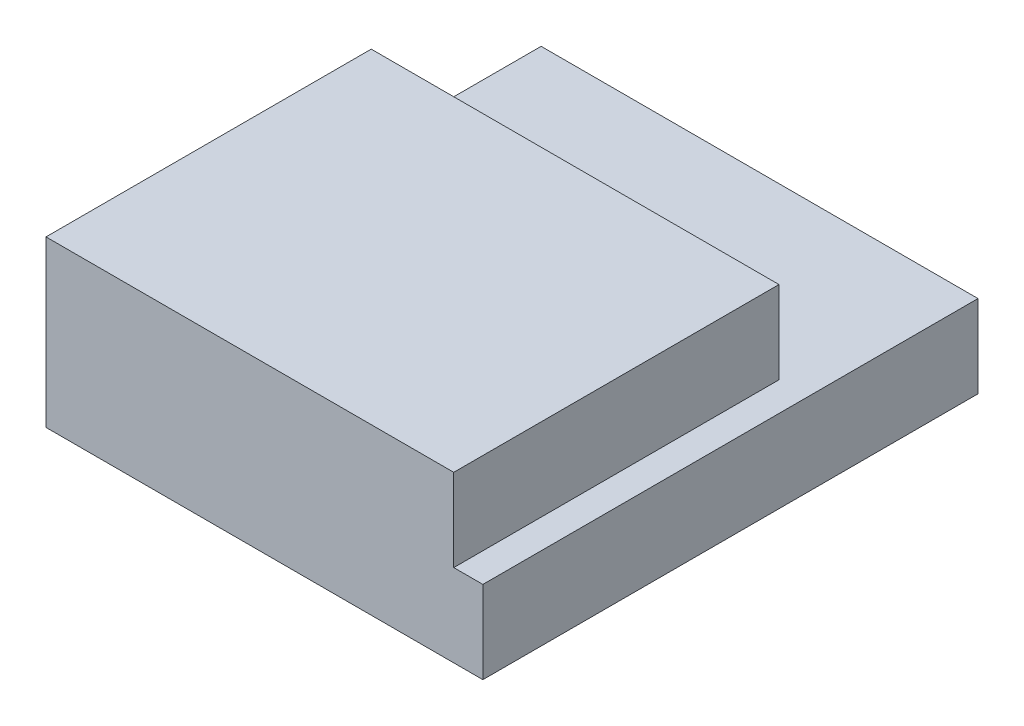
SolidWorks part; units mm, degrees
ref_plane "Front Plane" through (0, 0, 0) normal (0, 0, 1) x (1, 0, 0)
ref_plane "Top Plane" through (0, 0, 0) normal (0, 1, 0) x (1, 0, 0)
ref_plane "Right Plane" through (0, 0, 0) normal (1, 0, 0) x (0, 0, -1)
sketch "Sketch2" plane through (0, 0, 0) normal (0, 1, 0) x (1, 0, 0)
  line L1 (-16.125, 54.1875) -> (73.875, 54.1875)
  line L2 (-16.125, 54.1875) -> (-16.125, -47.8125)
  line L3 (-16.125, -47.8125) -> (73.875, -47.8125)
  line L4 (73.875, 54.1875) -> (73.875, -47.8125)
  dimension "D1" = 102
  dimension "D2" = 90
extrude "Boss-Extrude2" add sketch "Sketch2" along normal blind 17
sketch "Sketch3" plane through (0, 17, 0) normal (0, 1, 0) x (1, 0, 0)
  line L1 (-16.125, -47.8125) -> (67.875, -47.8125)
  line L2 (-16.125, -47.8125) -> (-16.125, 19.1875)
  line L3 (-16.125, 19.1875) -> (67.875, 19.1875)
  line L4 (67.875, -47.8125) -> (67.875, 19.1875)
  dimension "D1" = 84
  dimension "D2" = 67
extrude "Boss-Extrude3" add sketch "Sketch3" along normal blind 17
